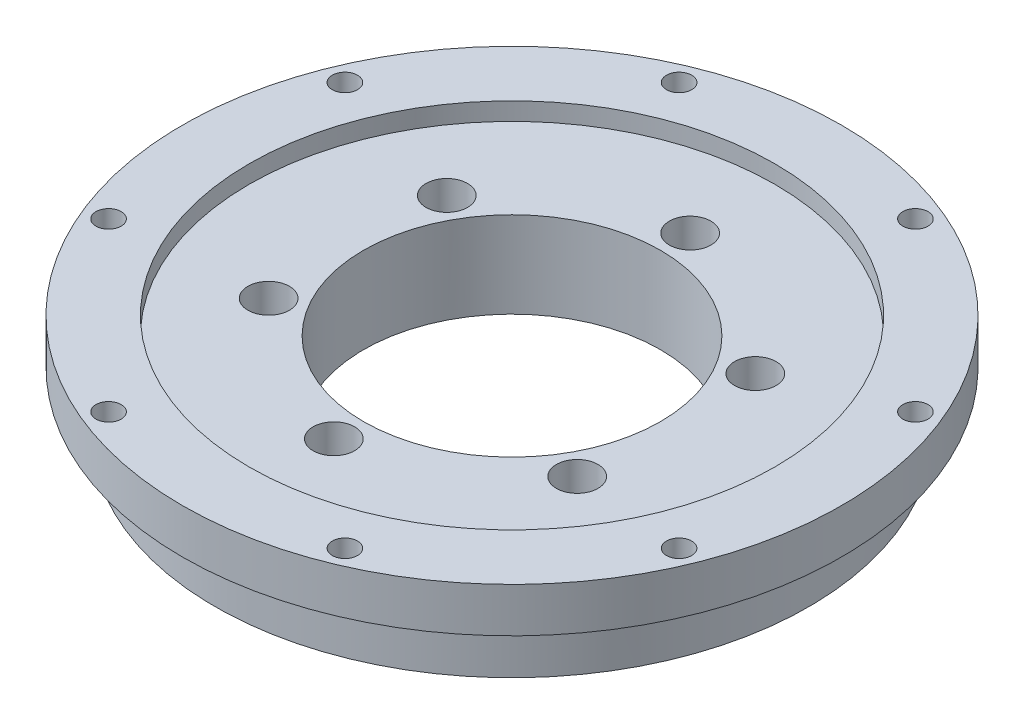
SolidWorks part; units mm, degrees
ref_plane "Front Plane" through (0, 0, 0) normal (0, 0, 1) x (1, 0, 0)
ref_plane "Top Plane" through (0, 0, 0) normal (0, 1, 0) x (1, 0, 0)
ref_plane "Right Plane" through (0, 0, 0) normal (1, 0, 0) x (0, 0, -1)
sketch "Sketch1" plane through (0, 0, 0) normal (0, 0, 1) x (1, 0, 0)
  line L0 (0, 0) -> (0, 67.3401) construction
  line L1 (50, 0) -> (50, 35)
  line L2 (50, 35) -> (111, 35)
  line L3 (111, 35) -> (111, 20)
  line L6 (100, 0) -> (50, 0)
  line L7 (111, 20) -> (100, 20)
  line L8 (100, 20) -> (100, 0)
  point P8 (0, 0)
  point P9 (123.2368, 33.4308)
  point P12 (111.6184, 20)
  dimension "D1" = 222
  dimension "D2" = 100
  dimension "D4" = 15
  dimension "D6" = 20
  dimension "D7" = 200
revolve "Revolve1" add sketch "Sketch1" angle 360 about L0
sketch "Sketch3" plane through (0, 0, 0) normal (0, -1, 0) x (1, 0, 0)
  line L0 (0, 0) -> (0, 60) construction
  circle A0 centre (0, 0) radius 60 construction
  circle A2 centre (0, 60) radius 5
  circle A3 centre (51.9615, 30) radius 5
  circle A4 centre (51.9615, -30) radius 5
  circle A5 centre (0, -60) radius 5
  circle A6 centre (-51.9615, -30) radius 5
  circle A7 centre (-51.9615, 30) radius 5
  point P5 (-46.2453, 19.0099)
  point P17 (0, 0)
  point P19 (14.5141, -3.1314)
  dimension "D1" = 120
  dimension "D2" = 10
  dimension "D3" = 6
extrude "Cut-Extrude1" cut sketch "Sketch3" against normal up to next
sketch "Sketch5" plane through (0, 35, 0) normal (0, 1, 0) x (1, 0, 0)
  circle A0 centre (0, 0) radius 88.5
  dimension "D1" = 177
extrude "Cut-Extrude3" cut sketch "Sketch5" against normal blind 6
sketch "Sketch4" plane through (0, 29, 0) normal (0, 1, 0) x (1, 0, 0)
  circle A1 centre (0, 60) radius 7
  circle A2 centre (0, 60) radius 5 construction
  circle A3 centre (51.9615, 30) radius 7
  circle A4 centre (51.9615, -30) radius 7
  circle A5 centre (0, -60) radius 7
  circle A6 centre (-51.9615, -30) radius 7
  circle A7 centre (-51.9615, 30) radius 7
  point P3 (-57.3506, -44.0467)
  point P6 (0, 0)
  point P16 (0, 0)
  dimension "D1" = 14
  dimension "D2" = 6
extrude "Cut-Extrude2" cut sketch "Sketch4" against normal blind 10
sketch "Sketch7" plane through (0, 20, 0) normal (0, -1, 0) x (1, 0, 0)
  line L0 (0, 0) -> (39.7991, 96.0835) construction
  line L1 (0, 0) -> (0, 104) construction
  circle A0 centre (0, 0) radius 104 construction
  dimension "D2" = 208
  dimension "D1" = 22.5
hole_wizard "M10 Tapped Hole1" positions "3DSketch1" profile "Sketch8" tap size "M10" standard "ISO"
sketch3d "3DSketch1"
  point P0 (39.7991, 20, 96.0835)
sketch "Sketch8" plane through (39.7991, 20, 96.0835) normal (1, 0, 0) x (0, 0, -1)
  line L0 (0, 0) -> (0, 27.0537)
  line L1 (0, 27.0537) -> (4.25, 24.5)
  line L2 (4.25, 24.5) -> (4.25, 0.775)
  line L3 (4.25, 0.775) -> (5.025, 0)
  line L5 (5.025, 0) -> (0, 0)
  line L6 (-4.25, 0.775) -> (-5.025, 0) construction
  line L10 (0, 27.0537) -> (-4.25, 24.5) construction
  line L11 (0, -6.35) -> (0, 107.95) construction
  dimension "Tap Drill Dia." = 8.5
  dimension "Tap Drill Depth" = 24.5
  dimension "Near C'Sink Dia." = 10.05
  dimension "Near C'Sink Angle" = 90
  dimension "Drill Angle" = 118
cosmetic thread "Hole Thread1" parameters "D1"=20, "D2"=10
pattern_circular "CirPattern1" count 8 over 360 about axis through (0, 0, 0) along (0, 1, 0) of "M10 Tapped Hole1"
cosmetic thread "Hole Thread2" parameters "D1"=20, "D2"=10
cosmetic thread "Hole Thread3" parameters "D1"=20, "D2"=10
cosmetic thread "Hole Thread4" parameters "D1"=20, "D2"=10
cosmetic thread "Hole Thread5" parameters "D1"=20, "D2"=10
cosmetic thread "Hole Thread6" parameters "D1"=20, "D2"=10
cosmetic thread "Hole Thread7" parameters "D1"=20, "D2"=10
cosmetic thread "Hole Thread8" parameters "D1"=20, "D2"=10
